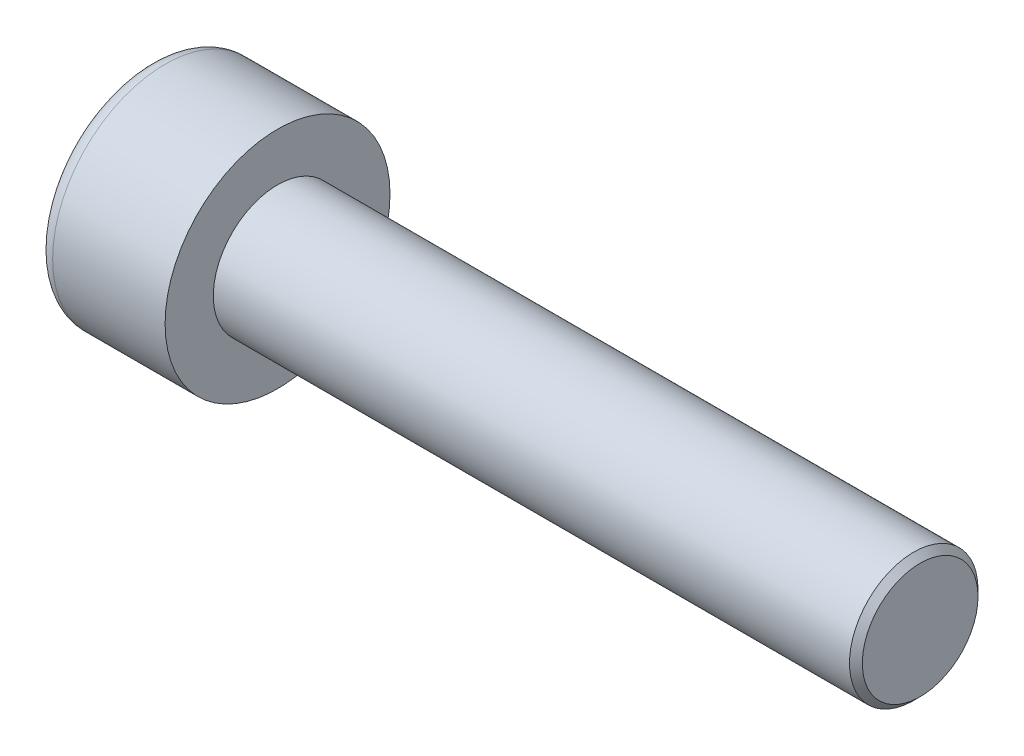
SolidWorks part; units mm, degrees
ref_plane "Front" through (0, 0, 0) normal (0, 0, 1) x (1, 0, 0)
ref_plane "Top" through (0, 0, 0) normal (0, 1, 0) x (1, 0, 0)
ref_plane "Right" through (0, 0, 0) normal (1, 0, 0) x (0, 0, -1)
sketch "Sketch1" plane through (0, 0, 0) normal (1, 0, 0) x (0, 0, -1)
  circle A0 centre (0, 0) radius 3.5
  dimension "dk" = 7
extrude "BaseHead" add sketch "Sketch1" along normal blind 4
sketch "Sketch2" plane through (4, 0, 0) normal (1, 0, 0) x (0, 0, -1)
  circle A0 centre (0, 0) radius 2
  dimension "d" = 4
extrude "BaseBody" add sketch "Sketch2" along normal blind 20
cosmetic thread "ThreadCosmetic1" [suppressed] parameters "b"=20, "D2"=3.242
sketch "Sketch3" plane through (0, 0, 0) normal (1, 0, 0) x (0, 0, -1)
  line L1 (1.7321, 0) -> (0.866, 1.5)
  line L2 (0.866, 1.5) -> (-0.866, 1.5)
  line L3 (-0.866, 1.5) -> (-1.7321, 0)
  line L4 (-1.7321, 0) -> (-0.866, -1.5)
  line L5 (-0.866, -1.5) -> (0.866, -1.5)
  line L6 (0.866, -1.5) -> (1.7321, 0)
  circle A0 centre (0, 0) radius 1.5 construction
  dimension "s" = 3
  dimension "e" = 3.4641
extrude "HexagonSocket" cut sketch "Sketch3" along normal blind 2
sketch "Sketch4" plane through (-4.1961, 0.75, 0) normal (0, 0, 1) x (-1, 0, 0)
  line L0 (-6.1961, 2.25) -> (-7.0622, 0.75)
  line L2 (-7.0622, 0.75) -> (-6.1961, 0.75)
  line L3 (-6.1961, 0.75) -> (-6.1961, 2.25)
  line L4 (-5.0351, 0.75) -> (0.839, 0.75) construction
  line L5 (-28.1961, 0.75) -> (-8.1961, 0.75) construction
  line L6 (-8.1961, 0.75) -> (-4.1961, 0.75) construction
  dimension "m" = 60
revolve "Cut-Revolve1" cut sketch "Sketch4" angle 360 about L4
fillet "HeadFillet" [suppressed] radius 0.2
fillet "TopFillet" radius 0.5 1 edges at (0, 0, -3.5)
chamfer "Chamfer1" distance 0.2 angle 45 1 edges at (24, 0, -2)
sketch "Sketch5" plane through (0, 0, 0) normal (0, 0, 1) x (1, 0, 0)
  line L0 (23.8, 1.6718) -> (23.9895, 2)
  line L1 (23.9895, 2) -> (23.9895, 2.379)
  line L2 (23.9895, 2.379) -> (23.6105, 2.379)
  line L3 (23.6105, 2.379) -> (23.6105, 2)
  line L4 (23.6105, 2) -> (23.8, 1.6718)
  line L5 (0, 0) -> (7.8886, 0) construction
  line L6 (23.8, -2) -> (23.8, 2) construction
  dimension "D1" = 4
  dimension "D2" = 0.379
revolve "Cut-Revolve10" [suppressed] cut sketch "Sketch5" angle 360 about L5
pattern_linear "LPattern10" [suppressed] count 44 spacing 0.4548 along (1, 0, 0)
equation "\"r1@TopFillet\" = \"d@Sketch2\" / 8"
equation "\"D1@Chamfer1\" = \"r@HeadFillet\""
equation "\"D1@Sketch5\" = \"d@Sketch2\""
equation "\"D2@Sketch5\" =  ( \"d@Sketch2\" - \"D2@ThreadCosmetic1\" )  / 2"
equation "\"D3@LPattern10\" = \"D2@Sketch5\" * 1.2"
equation "\"D1@LPattern10\" = \"b@ThreadCosmetic1\" / \"D3@LPattern10\""
